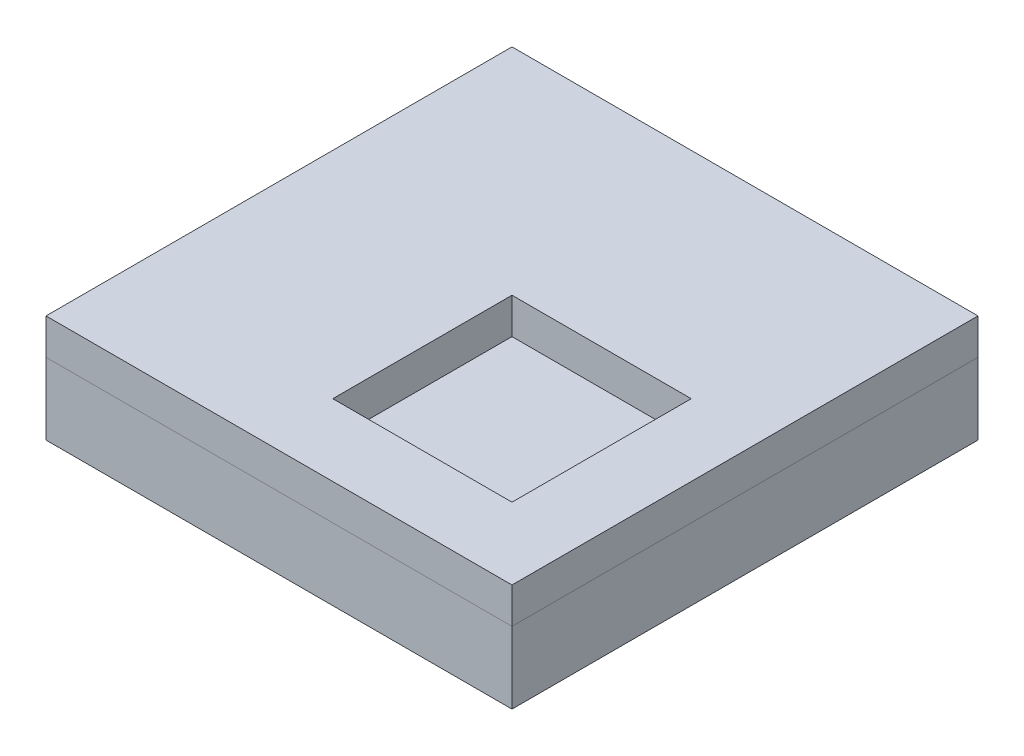
SolidWorks part; units mm, degrees
ref_plane "정면" through (0, 0, 0) normal (0, 0, 1) x (1, 0, 0)
ref_plane "윗면" through (0, 0, 0) normal (0, 1, 0) x (1, 0, 0)
ref_plane "우측면" through (0, 0, 0) normal (1, 0, 0) x (0, 0, -1)
sketch "스케치1" plane through (0, 0, 0) normal (0, 1, 0) x (1, 0, 0)
  line L1 (6.5, -6.5) -> (-6.5, -6.5)
  line L2 (6.5, -6.5) -> (6.5, 6.5)
  line L3 (6.5, 6.5) -> (-6.5, 6.5)
  line L4 (-6.5, -6.5) -> (-6.5, 6.5)
  line L5 (6.5, -6.5) -> (-6.5, 6.5) construction
  line L6 (6.5, 6.5) -> (-6.5, -6.5) construction
  point P0 (0, 0)
  dimension "D1" = 13
  dimension "D2" = 13
extrude "보스-돌출1" add sketch "스케치1" along normal blind 2
sketch "스케치2" plane through (0, 0, 0) normal (0, 1, 0) x (1, 0, 0)
  line L0 (-6.5, -6.5) -> (6.5, -6.5) construction
  line L1 (-5.5, 9.5) -> (5.5, 9.5)
  line L2 (-5.5, 9.5) -> (-5.5, -5.5)
  line L3 (-5.5, -5.5) -> (5.5, -5.5)
  line L4 (5.5, 9.5) -> (5.5, -5.5)
  line L5 (6.5, -6.5) -> (6.5, 6.5) construction
  dimension "D1" = 11
  dimension "D2" = 15
  dimension "D3" = 1
  dimension "D4" = 1
extrude "컷-돌출1" cut sketch "스케치2" along normal blind 3 from offset 1
sketch "스케치3" plane through (0, 0, 0) normal (0, 1, 0) x (1, 0, 0)
  line L1 (6.5, -6.5) -> (-6.5, -6.5)
  line L2 (6.5, -6.5) -> (6.5, 6.5)
  line L3 (6.5, 6.5) -> (-6.5, 6.5)
  line L4 (-6.5, -6.5) -> (-6.5, 6.5)
  line L5 (6.5, -6.5) -> (-6.5, 6.5) construction
  line L6 (6.5, 6.5) -> (-6.5, -6.5) construction
  point P0 (0, 0)
extrude "보스-돌출3" add sketch "스케치3" along normal blind 1 from offset 2 separate body
sketch "스케치4" plane through (0, 0, 0) normal (0, 1, 0) x (1, 0, 0)
  line L0 (-6.5, -6.5) -> (6.5, -6.5) construction
  line L1 (-0.5, 0.5) -> (4.5, 0.5)
  line L2 (-0.5, 0.5) -> (-0.5, -4.5)
  line L3 (-0.5, -4.5) -> (4.5, -4.5)
  line L4 (4.5, 0.5) -> (4.5, -4.5)
  line L5 (6.5, -6.5) -> (6.5, 6.5) construction
  dimension "D1" = 5
  dimension "D2" = 5
  dimension "D3" = 2
  dimension "D4" = 2
extrude "컷-돌출2" cut sketch "스케치4" against normal blind 1 from surface at 3 starting at face at (0, 3, 0)
